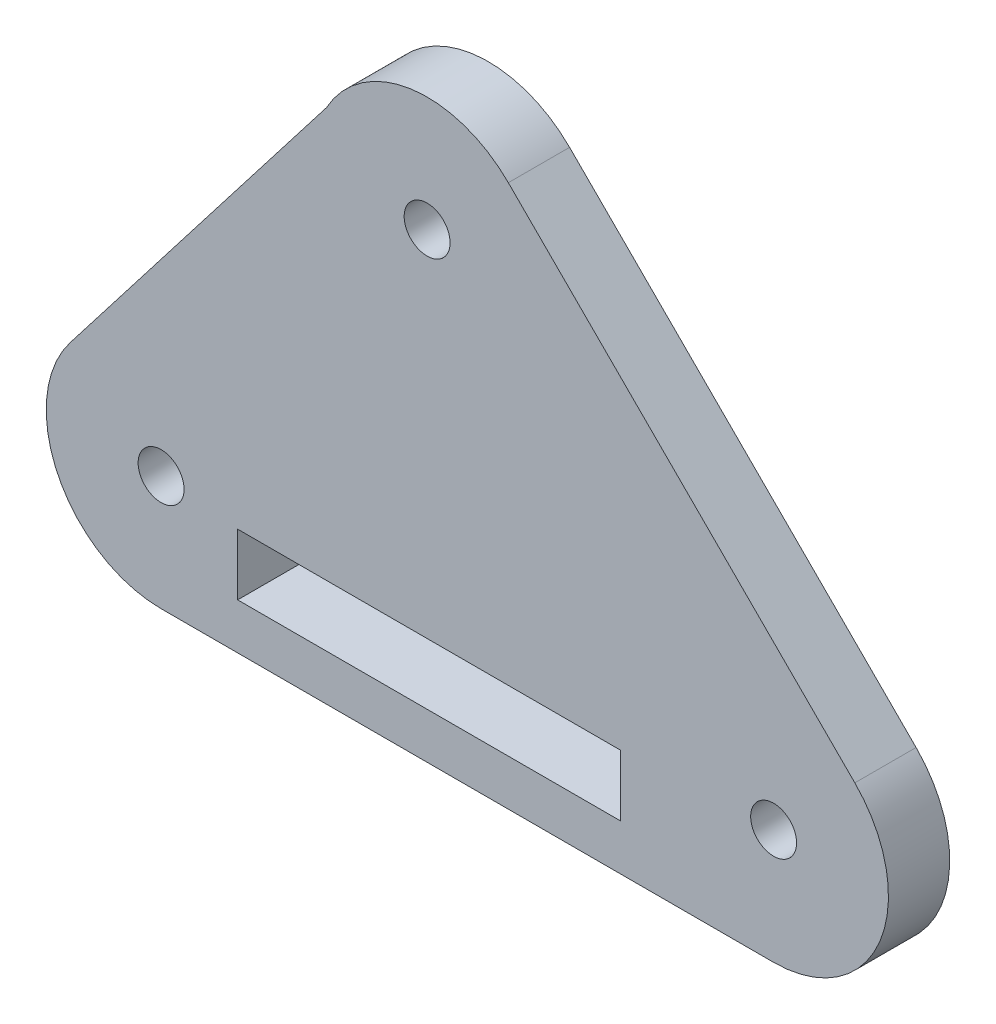
SolidWorks part; units mm, degrees
material "Acrílico (Impacto medio-alto)"
ref_plane "Piano frontale" through (0, 0, 0) normal (0, 0, 1) x (1, 0, 0)
ref_plane "Piano superiore" through (0, 0, 0) normal (0, 1, 0) x (1, 0, 0)
ref_plane "Piano destro" through (0, 0, 0) normal (1, 0, 0) x (0, 0, -1)
sketch "Schizzo1" plane through (0, 0, 0) normal (0, 0, 1) x (1, 0, 0)
  line L0 (-22.6274, -7.5) -> (0, -7.5)
  line L1 (-22.6274, 22.6274) -> (0, 0) construction
  line L2 (0, 0) -> (-22.6274, 0) construction
  line L3 (-29.2018, 26.2367) -> (-30.1227, 0.2658) construction
  line L4 (-17.3241, 27.9307) -> (5.3033, 5.3033)
  line L5 (-22.6274, 22.6274) -> (-22.6274, 0) construction
  line L6 (-45.9343, 4.5863) -> (-29.2018, 26.2367)
  line L7 (-10, -4.5) -> (-35, -4.5)
  line L8 (-10, -4.5) -> (-10, -0.5)
  line L9 (-10, -0.5) -> (-35, -0.5)
  line L10 (-35, -4.5) -> (-35, -0.5)
  line L11 (-10, -4.5) -> (-35, -0.5) construction
  line L12 (-10, -0.5) -> (-35, -4.5) construction
  line L13 (-40, -7.5) -> (-22.6274, -7.5)
  line L14 (-22.6274, 0) -> (-40, 0) construction
  line L15 (-40, 0) -> (-22.6274, 22.6274) construction
  circle A0 centre (0, 0) radius 1.5
  arc A1 (0, -7.5) -> (5.3033, 5.3033) centre (0, 0) ccw
  arc A2 (-29.2018, 26.2367) -> (-17.3241, 27.9307) centre (-22.6274, 22.6274) cw
  arc A3 (-30.1227, 0.2658) -> (-22.6274, -7.5) centre (-22.6274, 0) ccw construction
  circle A4 centre (-22.6274, 22.6274) radius 1.5
  circle A5 centre (-40, 0) radius 1.5
  arc A6 (-40, -7.5) -> (-45.9343, 4.5863) centre (-40, 0) cw
  point P5 (-22.5, -2.5)
  dimension "D1" = 3
  dimension "D2" = 90
  dimension "D3" = 4
  dimension "D4" = 3
  dimension "D6" = 3
  dimension "D7" = 7.5
  dimension "D8" = 10
  dimension "D9" = 40
  dimension "D10" = 32
  dimension "D12" = 7.5
  dimension "D13" = 7.5
  dimension "D5" = 25
  dimension "D11" = 45
extrude "Estrusione-Estrusione2" add sketch "Schizzo1" along normal blind 4
